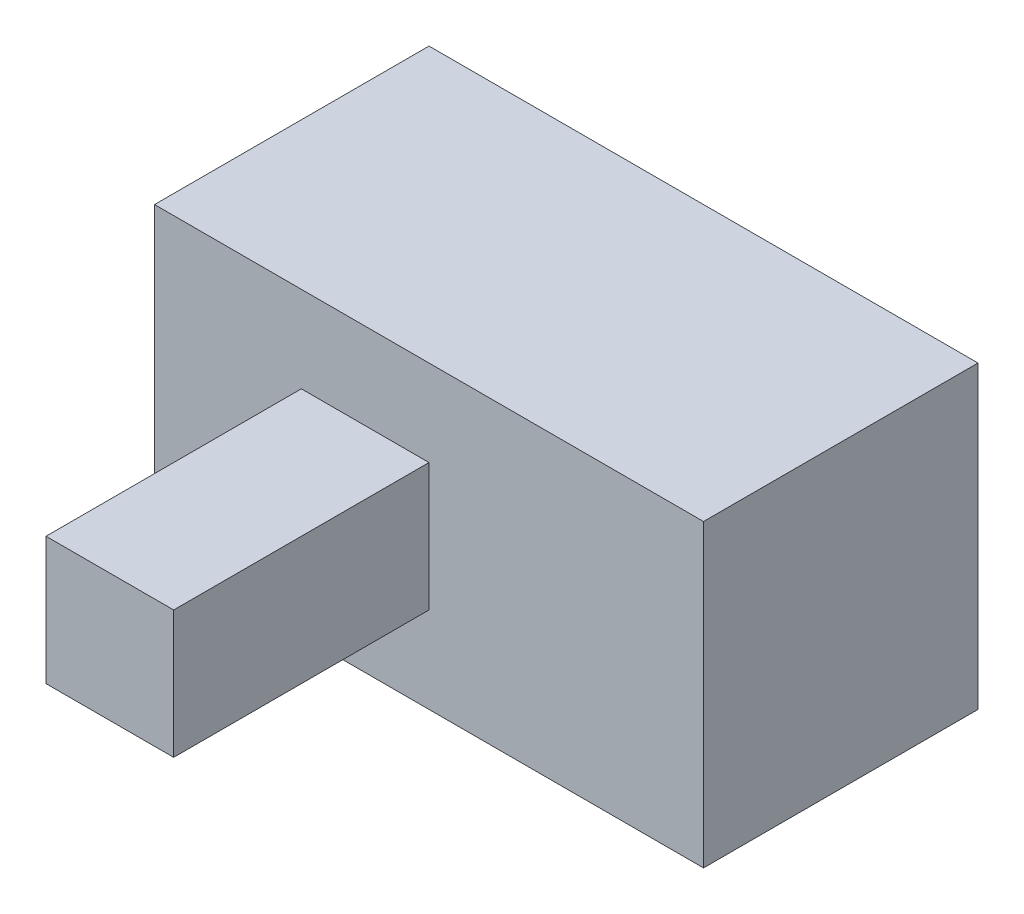
SolidWorks part; units mm, degrees
ref_plane "Front Plane" through (0, 0, 0) normal (0, 0, 1) x (1, 0, 0)
ref_plane "Top Plane" through (0, 0, 0) normal (0, 1, 0) x (1, 0, 0)
ref_plane "Right Plane" through (0, 0, 0) normal (1, 0, 0) x (0, 0, -1)
sketch "Sketch1" plane through (0, 0, 0) normal (0, 1, 0) x (1, 0, 0)
  line L1 (-4.3, -2.15) -> (4.3, -2.15)
  line L2 (-4.3, -2.15) -> (-4.3, 2.15)
  line L3 (-4.3, 2.15) -> (4.3, 2.15)
  line L4 (4.3, -2.15) -> (4.3, 2.15)
  line L5 (-4.3, -2.15) -> (4.3, 2.15) construction
  line L6 (-4.3, 2.15) -> (4.3, -2.15) construction
  point P0 (0, 0)
  dimension "D1" = 8.6
  dimension "D2" = 4.3
extrude "Boss-Extrude1" add sketch "Sketch1" along normal blind 4.7
sketch "Sketch2" plane through (0, 0, 2.15) normal (0, 0, 1) x (1, 0, 0)
  line L1 (-2, 1.35) -> (0, 1.35)
  line L2 (-2, 1.35) -> (-2, 3.35)
  line L3 (-2, 3.35) -> (0, 3.35)
  line L4 (0, 1.35) -> (0, 3.35)
  line L5 (-2, 1.35) -> (0, 3.35) construction
  line L6 (-2, 3.35) -> (0, 1.35) construction
  point P0 (-1, 2.35)
  dimension "D1" = 2
  dimension "D2" = 2
  dimension "D3" = 1
  dimension "D4" = 2.35
extrude "Boss-Extrude2" add sketch "Sketch2" along normal blind 4
sketch "Sketch3" plane through (0, 0, 0) normal (0, -1, 0) x (1, 0, 0)
  line L0 (4.3, -2.15) -> (-4.3, -2.15) construction
  circle A0 centre (-2, 0) radius 0.4
  circle A1 centre (0, 0) radius 0.4
  circle A2 centre (2, 0) radius 0.4
  dimension "D1" = 0.8
  dimension "D2" = 0.8
  dimension "D3" = 0.8
  dimension "D4" = 0
  dimension "D5" = 2.15
  dimension "D6" = 2.15
  dimension "D7" = 2.15
  dimension "D8" = 2
  dimension "D9" = 2
extrude "Boss-Extrude3" add sketch "Sketch3" along normal blind 1.5
